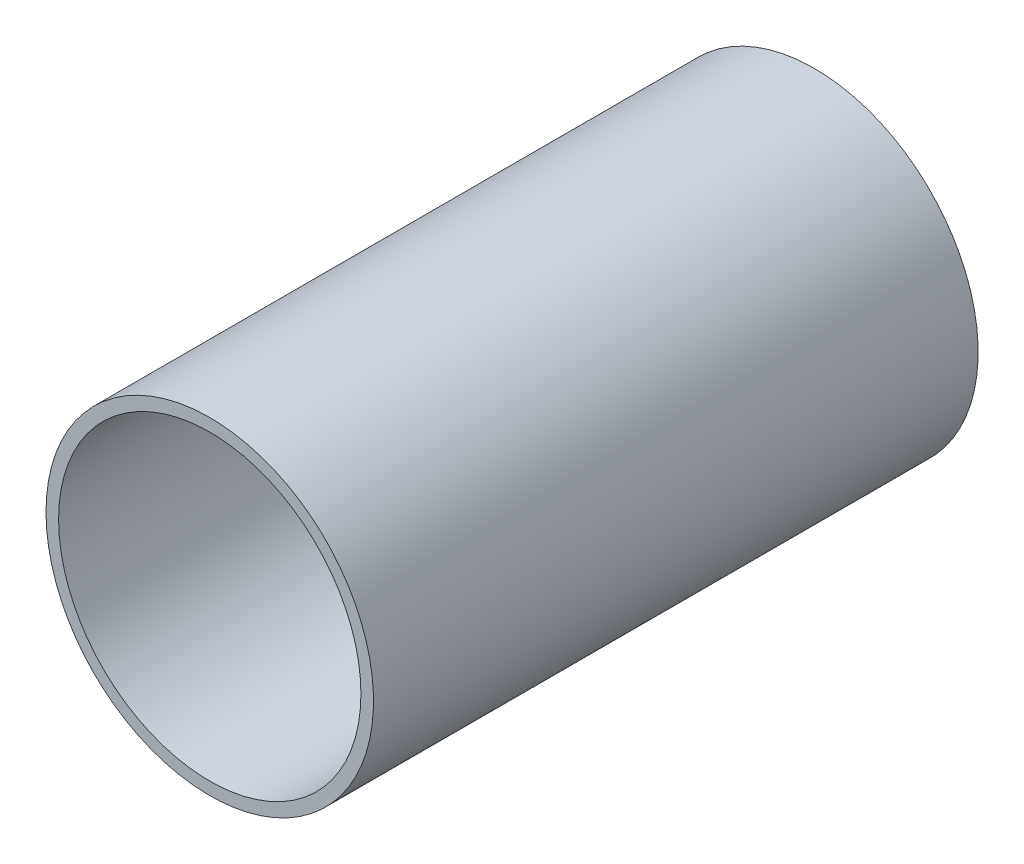
SolidWorks part; units mm, degrees
material "Acrylic (Medium-high impact)"
ref_plane "Front Plane" through (0, 0, 0) normal (0, 0, 1) x (1, 0, 0)
ref_plane "Top Plane" through (0, 0, 0) normal (0, 1, 0) x (1, 0, 0)
ref_plane "Right Plane" through (0, 0, 0) normal (1, 0, 0) x (0, 0, -1)
sketch "Sketch1" plane through (0, 0, 0) normal (0, 0, 1) x (1, 0, 0)
  circle A0 centre (0, 0) radius 82.55
  circle A1 centre (0, 0) radius 76.2
  dimension "D1" = 165.1
  dimension "D2" = 6.35
extrude "Boss-Extrude1" add sketch "Sketch1" along normal blind 304.8
